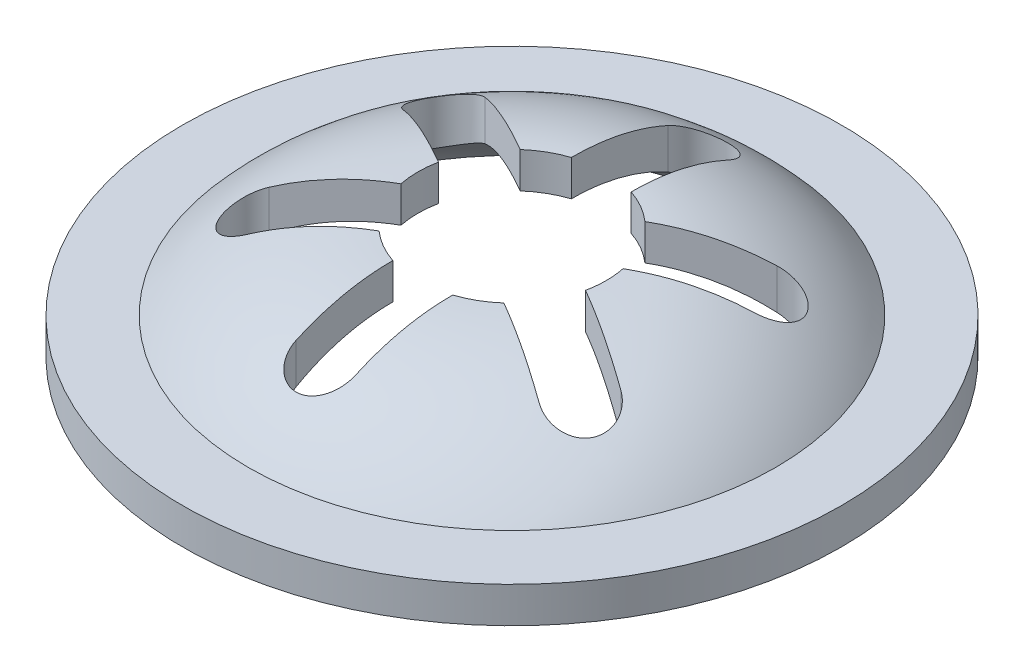
SolidWorks part; units mm, degrees
ref_plane "Front Plane" through (0, 0, 0) normal (0, 0, 1) x (1, 0, 0)
ref_plane "Top Plane" through (0, 0, 0) normal (0, 1, 0) x (1, 0, 0)
ref_plane "Right Plane" through (0, 0, 0) normal (1, 0, 0) x (0, 0, -1)
sketch "Sketch2" plane through (0, 0, 0) normal (0, 0, 1) x (1, 0, 0)
  line L0 (0, 0) -> (0, 1.2) construction
  line L1 (-3.5, 0) -> (-2.6174, 0)
  line L2 (-1, 1.2) -> (-1, 0.819)
  line L3 (-3.5, 0) -> (-3.5, 0.381)
  line L4 (-3.5, 0.381) -> (-2.8, 0.381)
  line L5 (0, 1.2) -> (-1, 1.2) construction
  arc A0 (-2.6174, 0) -> (-1, 0.819) centre (-1, -1.1875) cw
  arc A1 (-2.8, 0.381) -> (-1, 1.2) centre (-1, -1.1875) cw
  dimension "Ht" = 1.2
  dimension "OD" = 7
  dimension "D3" = 0.381
  dimension "D4" = 5.6
  dimension "Shaft Dia" = 2
revolve "Revolve1" add sketch "Sketch2" angle 360 about L0
sketch "Sketch3" plane through (0, 0, 0) normal (0, 1, 0) x (1, 0, 0)
  line L1 (-0.3175, 1.9745) -> (0.3175, 1.9745) construction
  line L2 (-0.3175, 1.9745) -> (-0.3175, 0)
  line L3 (-0.3175, 0) -> (0.3175, 0)
  line L4 (0.3175, 1.9745) -> (0.3175, 0)
  arc A0 (-0.3175, 1.9745) -> (0.3175, 1.9745) centre (0, 1.9745) cw
  circle A4 centre (0, 0) radius 2.292
  circle A5 centre (0, 0) radius 2.292 construction
  dimension "D2" = 0.635
  dimension "D1" = 0.508
extrude "Cut-Extrude1" cut sketch "Sketch3" along normal through all
pattern_circular "CirPattern1" count 6 over 360 about axis through (0, 0, 0) along (0, 1, 0) of "Cut-Extrude1"
equation "\"D4@Sketch2\" = \"OD@Sketch2\"*.8"
